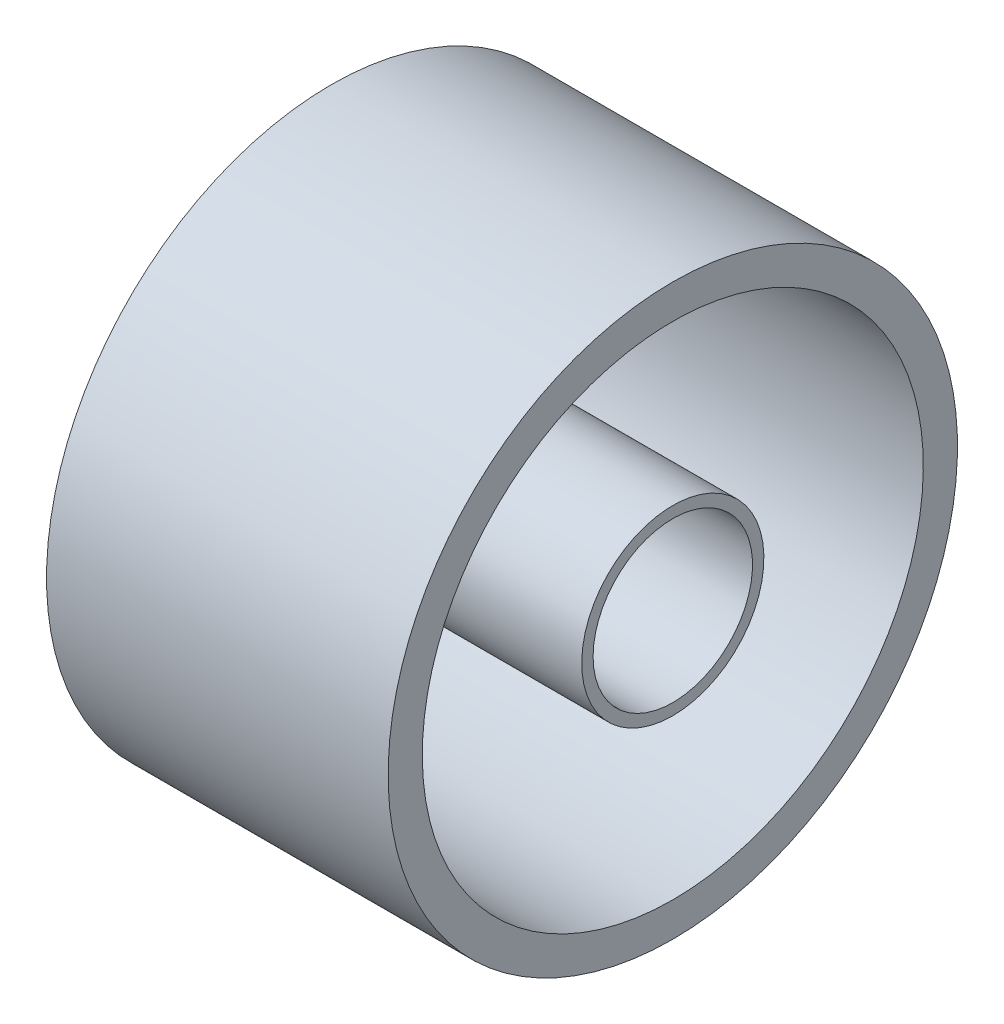
SolidWorks part; units mm, degrees
ref_plane "Plano frontal" through (0, 0, 0) normal (0, 0, 1) x (1, 0, 0)
ref_plane "Plano superior" through (0, 0, 0) normal (0, 1, 0) x (1, 0, 0)
ref_plane "Plano direito" through (0, 0, 0) normal (1, 0, 0) x (0, 0, -1)
sketch "Esboço1" plane through (0, 0, 0) normal (0, 0, 1) x (1, 0, 0)
  line L0 (0, 0) -> (0, -25)
  line L1 (0, -25) -> (30, -25)
  line L2 (30, -25) -> (30, 0)
  line L3 (30, 0) -> (0, 0)
  dimension "D1" = 25
  dimension "D2" = 30
revolve "Revolução1" add sketch "Esboço1" angle 360 about L3
sketch "Esboço2" plane through (0, 0, 0) normal (-1, 0, 0) x (0, 0, 1)
  line L0 (-23.4548, 0) -> (-7, 0) construction
  line L1 (-22.6864, -1) -> (-22.6864, 1) construction
  line L2 (-7.5469, 3.6352) -> (-7.5469, -3.6352) construction
  line L3 (0, -28.4766) -> (0, 28.4766) construction
  line L4 (-22.6864, -0.744) -> (-7.5469, -0.744)
  line L5 (-22.6864, -0.744) -> (-22.6864, 1)
  line L6 (-22.6864, 1) -> (-7.5469, 1)
  line L7 (-7.5469, -0.744) -> (-7.5469, 1)
  line L8 (22.6864, 1) -> (7.5469, 1)
  line L9 (7.5469, -0.744) -> (7.5469, 1) construction
  line L10 (22.6864, -0.744) -> (7.5469, -0.744)
  line L11 (22.6864, -0.744) -> (22.6864, 1) construction
  circle A0 centre (0, 0) radius 22
  circle A1 centre (0, 0) radius 7
  circle A2 centre (0, 0) radius 8
  point P10 (-22.6864, 0)
  point P13 (-7.5469, 0)
  point P20 (0, 0)
  dimension "D1" = 14
  dimension "D2" = 16
  dimension "D3" = 44
  dimension "D4" = 2
  dimension "D5" = 1
extrude "Corte-extrusão1" cut sketch "Esboço2" against normal through all contours A1
sketch "Esboço5" plane through (0, 0, 0) normal (-1, 0, 0) x (0, 0, 1)
  circle A0 centre (0, 0) radius 8
  circle A1 centre (0, 0) radius 22
  dimension "D1" = 44
  dimension "D2" = 16
extrude "Corte-extrusão3" cut sketch "Esboço5" against normal through all
sketch "Esboço6" plane through (0, 0, 0) normal (-1, 0, 0) x (0, 0, 1)
  line L13 (8, 0) -> (-22, 0)
  line L15 (0, 7) -> (0, -7)
  line L16 (-22, 0) -> (-7, 0)
  line L17 (-22, 0) -> (-22, 2)
  line L18 (-22, 2) -> (-7, 2)
  line L19 (-7, 0) -> (-7, 2)
  line L20 (22, 2) -> (7, 2)
  line L21 (7, 0) -> (7, 2)
  line L22 (22, 0) -> (7, 0)
  line L23 (22, 0) -> (22, 2)
  circle A0 centre (0, 0) radius 7 construction
  circle A5 centre (0, 0) radius 22 construction
  point P3 (-7, 0)
  point P9 (-7, 0)
  point P10 (0, 0)
  point P13 (-22, 0)
  point P15 (0, 0)
  point P25 (0, 0)
  dimension "D1" = 15
  dimension "D2" = 2
extrude "Ressalto-extrusão2" add sketch "Esboço6" against normal blind 2 contours L17 L18 L19 L16 | L20 L21 L22 L23
